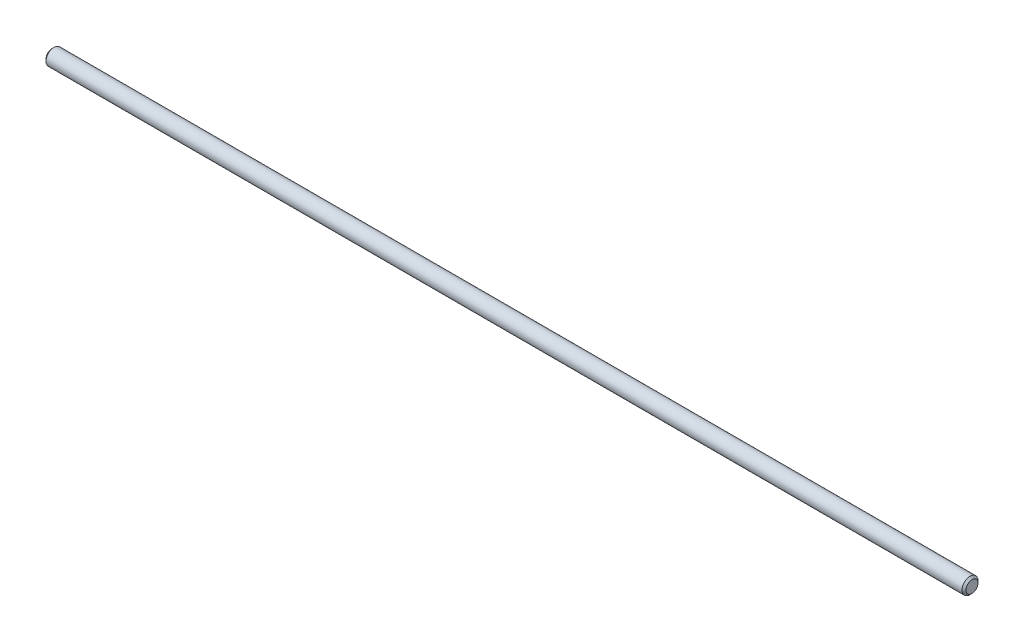
SolidWorks part; units mm, degrees
ref_plane "Front Plane" through (0, 0, 0) normal (0, 0, 1) x (1, 0, 0)
ref_plane "Top Plane" through (0, 0, 0) normal (0, 1, 0) x (1, 0, 0)
ref_plane "Right Plane" through (0, 0, 0) normal (1, 0, 0) x (0, 0, -1)
sketch "Sketch1" plane through (0, 0, 0) normal (1, 0, 0) x (0, 0, -1)
  circle A0 centre (0, 0) radius 4
  dimension "D1" = 8
extrude "Boss-Extrude1" add sketch "Sketch1" along normal mid plane 460
chamfer "Chamfer1" distance 1 angle 45 2 edges at (230, 0, -4) (-230, 0, -4)
